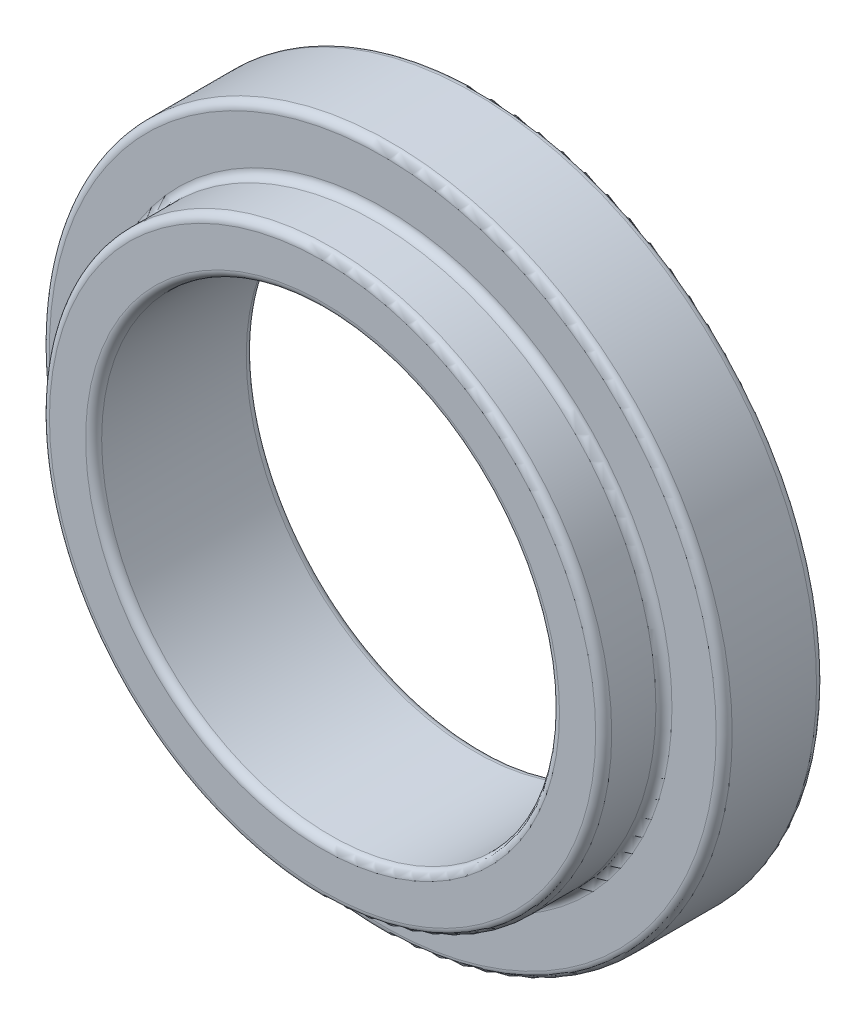
SolidWorks part; units mm, degrees
ref_plane "前视基准面" through (0, 0, 0) normal (0, 0, 1) x (1, 0, 0)
ref_plane "上视基准面" through (0, 0, 0) normal (0, 1, 0) x (1, 0, 0)
ref_plane "右视基准面" through (0, 0, 0) normal (1, 0, 0) x (0, 0, -1)
sketch "草图1" plane through (0, 0, 0) normal (0, 0, 1) x (1, 0, 0)
  circle A0 centre (0, 0) radius 85
  dimension "D1" = 170
extrude "凸台-拉伸1" add sketch "草图1" along normal blind 40
sketch "草图2" plane through (0, 0, 40) normal (0, 0, 1) x (1, 0, 0)
  circle A0 centre (0, 0) radius 57
  dimension "D1" = 114
extrude "切除-拉伸1" cut sketch "草图2" against normal through all
sketch "草图3" plane through (0, 0, 40) normal (0, 0, 1) x (1, 0, 0)
  circle A0 centre (0, 0) radius 85 construction
  circle A1 centre (0, 0) radius 85
  circle A2 centre (0, 0) radius 70
  dimension "D1" = 15
extrude "切除-拉伸2" cut sketch "草图3" against normal blind 15
fillet "圆角1" radius 2 6 edges at (85, 0, 0) (57, 0, 0) (70, 0, 40) (57, 0, 40) (85, 0, 25) (70, 0, 25)
